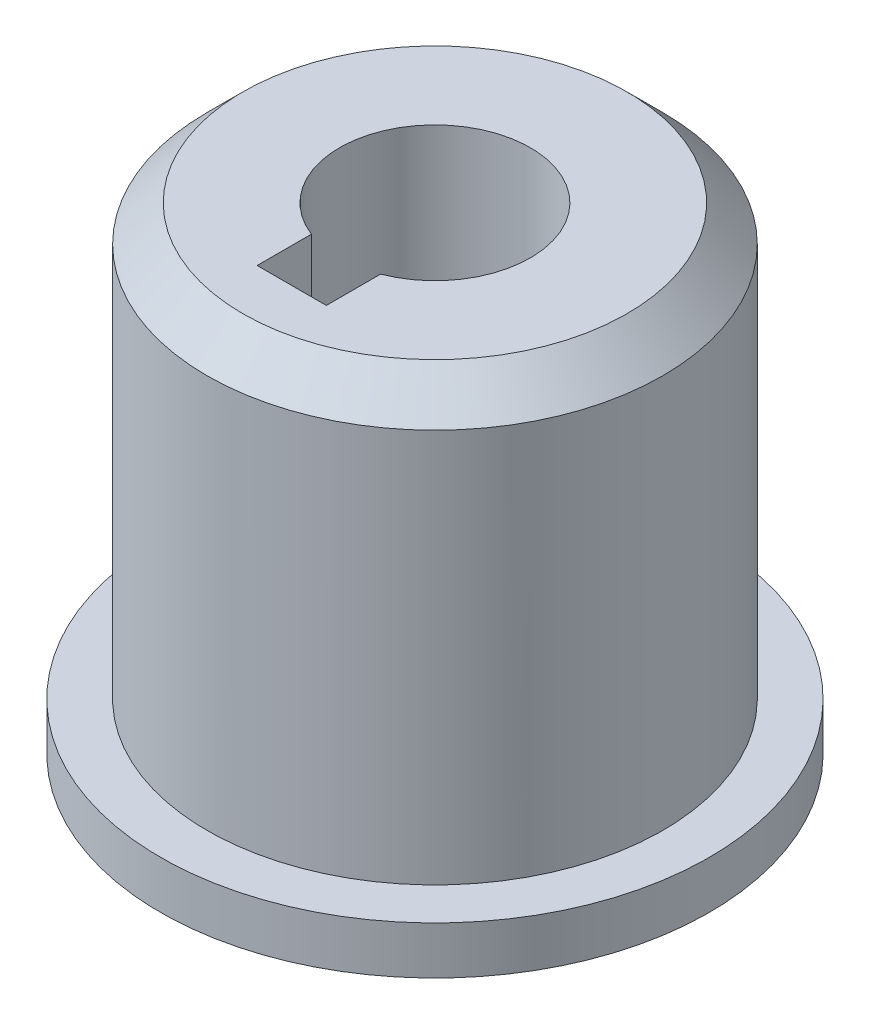
SolidWorks part; units mm, degrees
ref_plane "Front Plane" through (0, 0, 0) normal (0, 0, 1) x (1, 0, 0)
ref_plane "Top Plane" through (0, 0, 0) normal (0, 1, 0) x (1, 0, 0)
ref_plane "Right Plane" through (0, 0, 0) normal (1, 0, 0) x (0, 0, -1)
sketch "Sketch1" plane through (0, 0, 0) normal (0, 1, 0) x (1, 0, 0)
  line L1 (-1.45, -6) -> (1.45, -6)
  line L5 (0, -6) -> (0, -4) construction
  line L8 (-1.45, -6) -> (-1.45, -3.7279)
  line L10 (1.45, -6) -> (1.45, -3.7279)
  circle A0 centre (0, 0) radius 9.55
  arc A1 (1.45, -3.7279) -> (-1.45, -3.7279) centre (0, 0) ccw
  circle A2 centre (0, 0) radius 4 construction
  dimension "D1" = 19.1
  dimension "D2" = 8
  dimension "D3" = 6
  dimension "D4" = 2.9
extrude "Boss-Extrude1" add sketch "Sketch1" along normal blind 20
chamfer "Chamfer1" distance 1.5 angle 45 1 edges at (0, 20, 9.55)
sketch "Sketch2" plane through (0, 0, 0) normal (0, -1, 0) x (1, 0, 0)
  circle A2 centre (0, 0) radius 11.5
  circle A3 centre (0, 0) radius 9.55
  dimension "D1" = 23
extrude "Boss-Extrude2" add sketch "Sketch2" against normal blind 2
